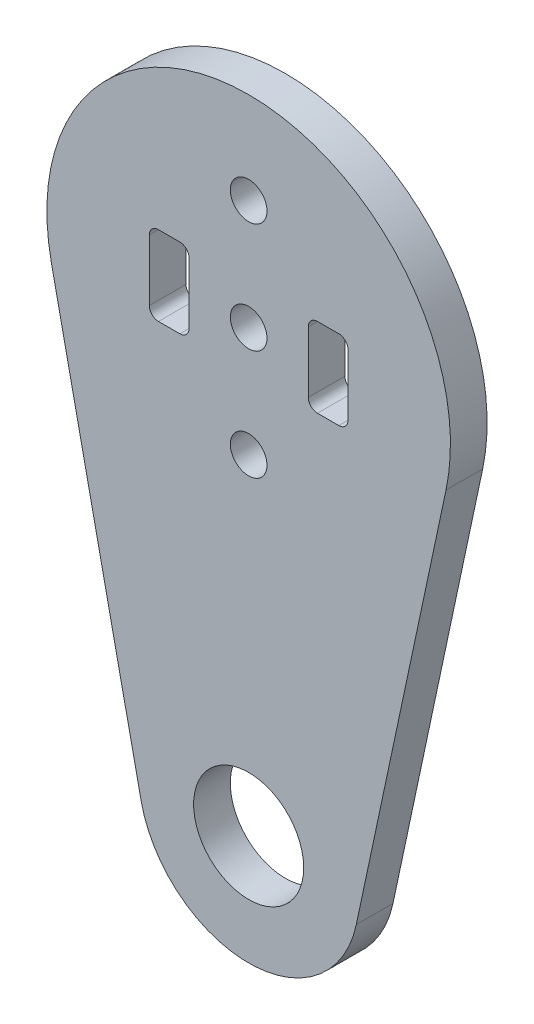
SolidWorks part; units mm, degrees
ref_plane "Alzado" through (0, 0, 0) normal (0, 0, 1) x (1, 0, 0)
ref_plane "Planta" through (0, 0, 0) normal (0, 1, 0) x (1, 0, 0)
ref_plane "Vista lateral" through (0, 0, 0) normal (1, 0, 0) x (0, 0, -1)
sketch "Model" plane through (0, 0, 0) normal (0, 0, 1) x (1, 0, 0)
  line L0 (223.1228, 245.202) -> (221.3728, 245.202)
  line L1 (223.8728, 239.452) -> (223.8728, 244.452)
  line L2 (221.3728, 238.702) -> (223.1228, 238.702)
  line L3 (220.6228, 244.452) -> (220.6228, 239.452)
  line L4 (208.3728, 245.202) -> (210.1228, 245.202)
  line L5 (207.6228, 239.452) -> (207.6228, 244.452)
  line L6 (210.1228, 238.702) -> (208.3728, 238.702)
  line L7 (210.8728, 244.452) -> (210.8728, 239.452)
  line L8 (206.9453, 204.077) -> (199.6099, 238.5145)
  line L9 (231.8858, 238.5145) -> (224.5503, 204.077)
  circle A0 centre (215.7478, 241.952) radius 1.5
  circle A1 centre (215.7478, 232.952) radius 1.5
  circle A2 centre (215.7478, 250.952) radius 1.5
  arc A3 (221.3728, 245.202) -> (220.6228, 244.452) centre (221.3728, 244.452) ccw
  arc A4 (223.8728, 244.452) -> (223.1228, 245.202) centre (223.1228, 244.452) ccw
  arc A5 (223.1228, 238.702) -> (223.8728, 239.452) centre (223.1228, 239.452) ccw
  arc A6 (220.6228, 239.452) -> (221.3728, 238.702) centre (221.3728, 239.452) ccw
  arc A7 (210.8728, 244.452) -> (210.1228, 245.202) centre (210.1228, 244.452) ccw
  arc A8 (208.3728, 245.202) -> (207.6228, 244.452) centre (208.3728, 244.452) ccw
  arc A9 (207.6228, 239.452) -> (208.3728, 238.702) centre (208.3728, 239.452) ccw
  arc A10 (210.1228, 238.702) -> (210.8728, 239.452) centre (210.1228, 239.452) ccw
  circle A11 centre (215.7478, 205.952) radius 4.5
  arc A12 (206.9453, 204.077) -> (224.5503, 204.077) centre (215.7478, 205.952) ccw
  arc A13 (231.8858, 238.5145) -> (199.6099, 238.5145) centre (215.7478, 241.952) ccw
extrude "Saliente-Extruir1" add sketch "Model" along normal blind 3
